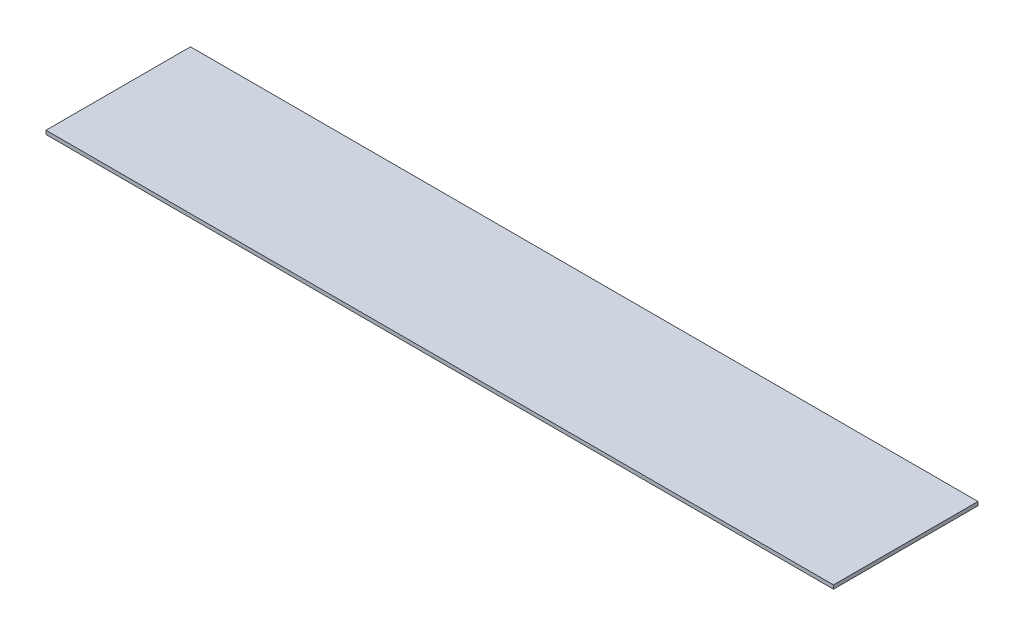
SolidWorks part; units mm, degrees
ref_plane "Front Plane" through (0, 0, 0) normal (0, 0, 1) x (1, 0, 0)
ref_plane "Top Plane" through (0, 0, 0) normal (0, 1, 0) x (1, 0, 0)
ref_plane "Right Plane" through (0, 0, 0) normal (1, 0, 0) x (0, 0, -1)
sketch "Sketch1" plane through (0, 0, 0) normal (0, 1, 0) x (1, 0, 0)
  line L1 (-59.1289, 156.3918) -> (947.993, 156.3918)
  line L2 (-59.1289, 156.3918) -> (-59.1289, -28.4005)
  line L3 (-59.1289, -28.4005) -> (947.993, -28.4005)
  line L4 (947.993, 156.3918) -> (947.993, -28.4005)
  dimension "D1" = 1007.1219
  dimension "D2" = 184.7924
extrude "Boss-Extrude2" add sketch "Sketch1" along normal blind 4.7625
